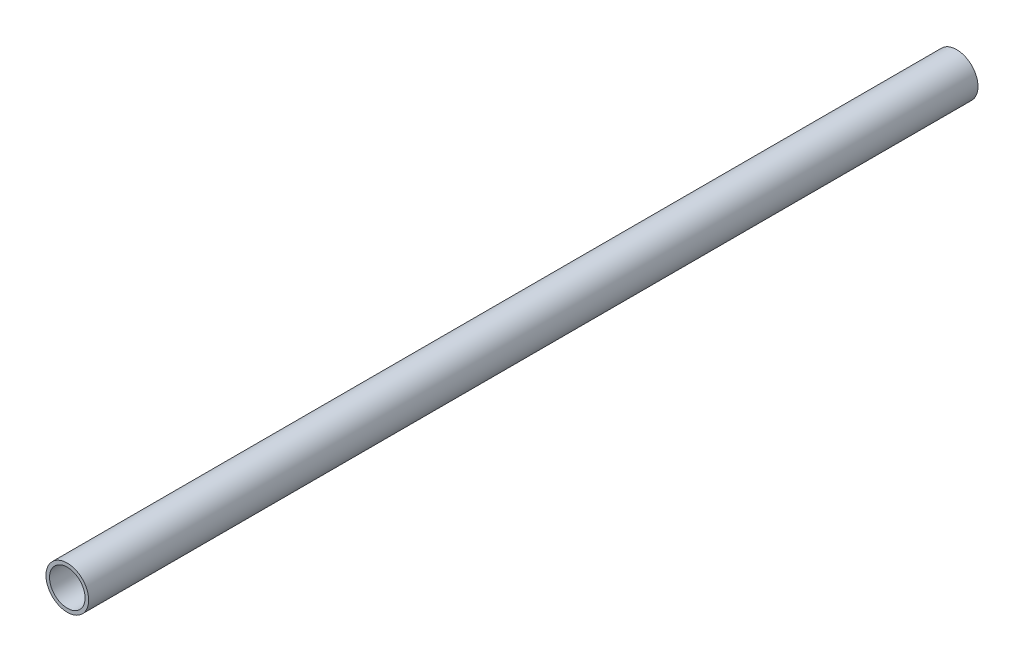
SolidWorks part; units mm, degrees
ref_plane "Front Plane" through (0, 0, 0) normal (0, 0, 1) x (1, 0, 0)
ref_plane "Top Plane" through (0, 0, 0) normal (0, 1, 0) x (1, 0, 0)
ref_plane "Right Plane" through (0, 0, 0) normal (1, 0, 0) x (0, 0, -1)
sketch "Sketch1" plane through (0, 0, 0) normal (0, 0, 1) x (1, 0, 0)
  circle A0 centre (0, 0) radius 6
  circle A1 centre (0, 0) radius 5
  dimension "D1" = 12
  dimension "D2" = 10
extrude "Boss-Extrude1" add sketch "Sketch1" along normal mid plane 250
